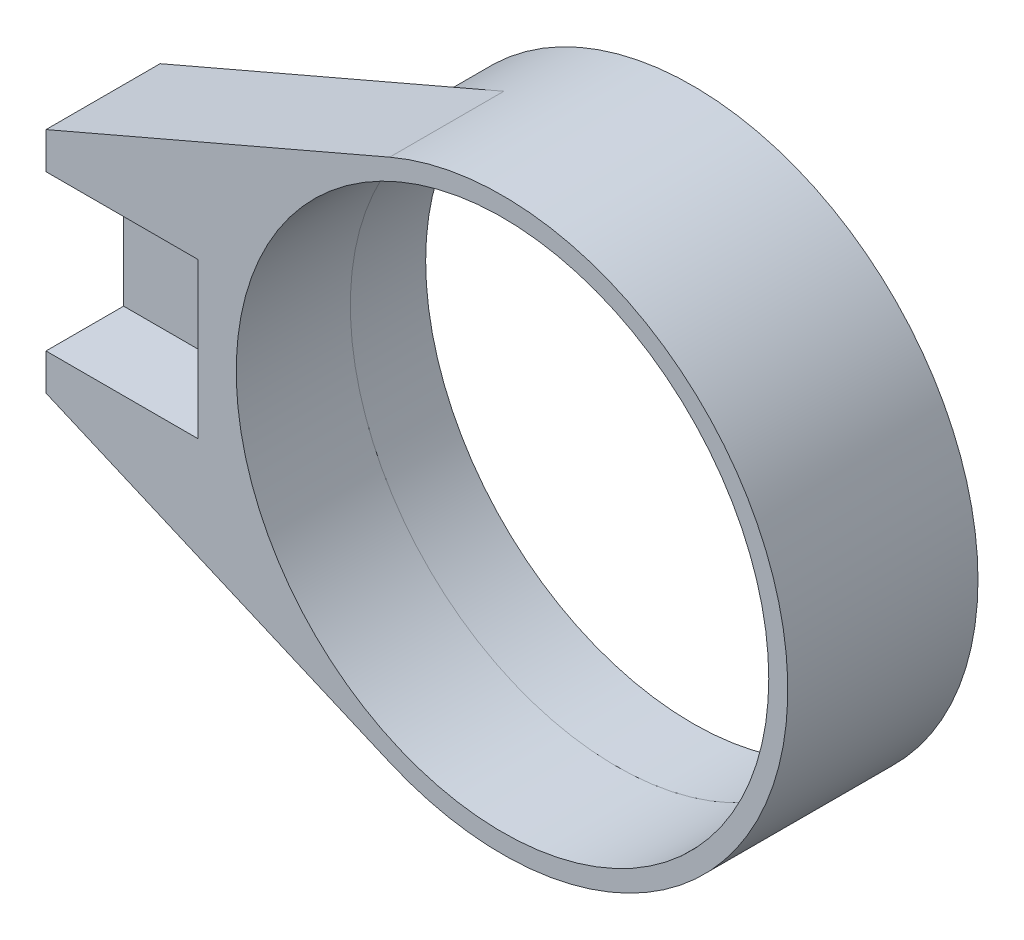
SolidWorks part; units mm, degrees
ref_plane "Plan de face" through (0, 0, 0) normal (0, 0, 1) x (1, 0, 0)
ref_plane "Plan de dessus" through (0, 0, 0) normal (0, 1, 0) x (1, 0, 0)
ref_plane "Plan de droite" through (0, 0, 0) normal (1, 0, 0) x (0, 0, -1)
sketch "Esquisse1" plane through (0, 0, 0) normal (0, 0, 1) x (1, 0, 0)
  circle A0 centre (0, 0) radius 35.1
  circle A1 centre (0, 0) radius 37.5
  dimension "D1" = 75
  dimension "D2" = 70.2
extrude "Boss.-Extru.1" add sketch "Esquisse1" along normal blind 10
sketch "Esquisse2" plane through (0, 0, 10) normal (0, 0, 1) x (1, 0, 0)
  line L0 (-1000, 0) -> (49000, 0) construction
  line L1 (-60, -15) -> (-60, 15)
  line L2 (-60, 15) -> (-14.8264, 34.4446)
  line L3 (-60, -15) -> (-14.8264, -34.4446)
  circle A0 centre (0, 0) radius 37.5 construction
  arc A1 (-14.8264, -34.4446) -> (-14.8264, 34.4446) centre (0, 0) ccw
  circle A2 centre (0, 0) radius 35
  point P11 (-60, 0)
  dimension "D1" = 70
  dimension "D2" = 15
  dimension "D3" = 60
extrude "Boss.-Extru.2" add sketch "Esquisse2" along normal blind 15
sketch "Esquisse6" plane through (-60, 0, 0) normal (-1, 0, 0) x (0, 0, 1)
  line L0 (25, 10) -> (15, 10) construction
  line L1 (25, 15) -> (25, -15) construction
  line L2 (15, 10) -> (15, -10) construction
  line L3 (-1000, 0) -> (49000, 0) construction
  line L4 (25, 15) -> (10, 15) construction
  line L5 (10, 15) -> (10, -15) construction
  line L6 (25, -10) -> (15, -10) construction
  line L7 (25, 10.2) -> (14.8, 10.2)
  line L8 (14.8, 10.2) -> (14.8, -10.2)
  line L9 (25, -10.2) -> (14.8, -10.2)
  line L10 (25, 10.2) -> (25, -10.2)
  point P16 (15, 0)
  dimension "D1" = 5
  dimension "D2" = 5
  dimension "D3" = 0.2
extrude "Enlèv. mat.-Extru.1" cut sketch "Esquisse6" against normal blind 20
